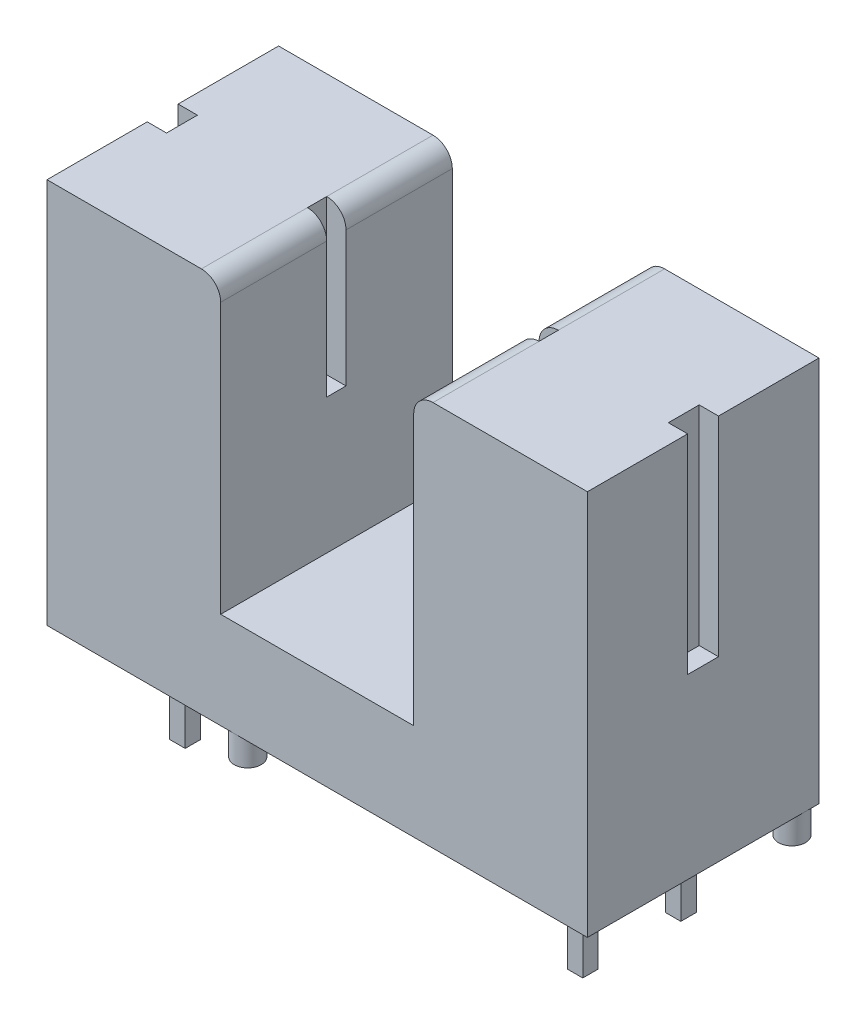
SolidWorks part; units mm, degrees
ref_plane "前视基准面" through (0, 0, 0) normal (0, 0, 1) x (1, 0, 0)
ref_plane "上视基准面" through (0, 0, 0) normal (0, 1, 0) x (1, 0, 0)
ref_plane "右视基准面" through (0, 0, 0) normal (1, 0, 0) x (0, 0, -1)
sketch "草图1" plane through (0, 0, 0) normal (0, 0, 1) x (1, 0, 0)
  line L0 (0, 6.704) -> (0, -11.7189) construction
  line L1 (-7, 5) -> (-2.5, 5)
  line L2 (-7, 5) -> (-7, -5)
  line L3 (-7, -5) -> (7, -5)
  line L4 (7, 5) -> (7, -5)
  line L5 (-7, 5) -> (7, -5) construction
  line L6 (-7, -5) -> (7, 5) construction
  line L7 (2.5, 5) -> (7, 5)
  line L9 (-2.5, 5) -> (-2.5, -2.5)
  line L10 (-2.5, -2.5) -> (2.5, -2.5)
  line L11 (2.5, 5) -> (2.5, -2.5)
  point P0 (0, 0)
  dimension "D1" = 14
  dimension "D2" = 10
  dimension "D3" = 5
  dimension "D4" = 2.5
extrude "凸台-拉伸1" add sketch "草图1" along normal blind 6
fillet "圆角1" radius 0.5 2 edges at (2.5, 5, 3) (-2.5, 5, 3)
sketch "草图2" plane through (0, -5, 0) normal (0, -1, 0) x (1, 0, 0)
  line L0 (-8.0802, 3) -> (8.1696, 3) construction
  line L1 (0, 6.3864) -> (0, -1.1649) construction
  line L3 (-5.15, 4.27) -> (5.15, 4.27) construction
  line L4 (-5.15, 4.27) -> (-5.15, 1.73) construction
  line L5 (-5.15, 1.73) -> (5.15, 1.73) construction
  line L6 (5.15, 4.27) -> (5.15, 1.73) construction
  line L7 (-5.15, 4.27) -> (5.15, 1.73) construction
  line L8 (-5.15, 1.73) -> (5.15, 4.27) construction
  line L9 (-5.35, 4.47) -> (-4.95, 4.47)
  line L10 (-5.35, 4.47) -> (-5.35, 4.07)
  line L11 (-5.35, 4.07) -> (-4.95, 4.07)
  line L12 (-4.95, 4.47) -> (-4.95, 4.07)
  line L13 (-5.35, 4.47) -> (-4.95, 4.07) construction
  line L14 (-5.35, 4.07) -> (-4.95, 4.47) construction
  line L15 (4.95, 4.47) -> (5.35, 4.47)
  line L16 (4.95, 4.47) -> (4.95, 4.07)
  line L17 (4.95, 4.07) -> (5.35, 4.07)
  line L18 (5.35, 4.47) -> (5.35, 4.07)
  line L19 (4.95, 4.47) -> (5.35, 4.07) construction
  line L20 (4.95, 4.07) -> (5.35, 4.47) construction
  line L21 (-5.35, 1.53) -> (-4.95, 1.53)
  line L22 (-5.35, 1.53) -> (-5.35, 1.93)
  line L23 (-5.35, 1.93) -> (-4.95, 1.93)
  line L24 (-4.95, 1.53) -> (-4.95, 1.93)
  line L25 (-5.35, 1.53) -> (-4.95, 1.93) construction
  line L26 (-5.35, 1.93) -> (-4.95, 1.53) construction
  line L27 (4.95, 1.93) -> (5.35, 1.93)
  line L28 (4.95, 1.93) -> (4.95, 1.53)
  line L29 (4.95, 1.53) -> (5.35, 1.53)
  line L30 (5.35, 1.93) -> (5.35, 1.53)
  line L31 (4.95, 1.93) -> (5.35, 1.53) construction
  line L32 (4.95, 1.53) -> (5.35, 1.93) construction
  point P4 (0, 3)
  dimension "D1" = 10.3
  dimension "D2" = 2.54
  dimension "D3" = 0.4
  dimension "D4" = 0.4
  dimension "D5" = 0.4
  dimension "D6" = 0.4
  dimension "D7" = 0.4
  dimension "D8" = 0.4
  dimension "D9" = 0.4
  dimension "D10" = 0.4
extrude "凸台-拉伸2" add sketch "草图2" along normal blind 2.5
sketch "草图3" plane through (-7, 0, 0) normal (-1, 0, 0) x (0, 0, 1)
  line L0 (3.0034, 5.5455) -> (3.0034, -0.195) construction
  line L1 (6, 5) -> (0, 5) construction
  line L2 (2.6034, 5) -> (3.4034, 5)
  line L3 (2.6034, 5) -> (2.6034, -0.4)
  line L4 (2.6034, -0.4) -> (3.4034, -0.4)
  line L5 (3.4034, 5) -> (3.4034, -0.4)
  dimension "D1" = 0.8
  dimension "D2" = 5.4
extrude "切除-拉伸1" cut sketch "草图3" against normal blind 0.5
sketch "草图4" plane through (7, 0, 0) normal (1, 0, 0) x (0, 0, -1)
  line L1 (-3.4034, 5) -> (-2.6034, 5)
  line L2 (-3.4034, 5) -> (-3.4034, -0.4)
  line L3 (-3.4034, -0.4) -> (-2.6034, -0.4)
  line L4 (-2.6034, 5) -> (-2.6034, -0.4)
extrude "切除-拉伸2" cut sketch "草图4" against normal blind 0.5
sketch "草图5" plane through (-2.5, 0, 0) normal (1, 0, 0) x (0, 0, -1)
  line L0 (-3.0034, 5.9062) -> (-3.0034, -8.6513) construction
  line L1 (-2.6034, 5) -> (-3.4034, 5) construction
  line L2 (-3.2534, 5) -> (-2.7534, 5)
  line L3 (-3.2534, 5) -> (-3.2534, 1)
  line L4 (-3.2534, 1) -> (-2.7534, 1)
  line L5 (-2.7534, 5) -> (-2.7534, 1)
  dimension "D1" = 0.5
  dimension "D2" = 4
extrude "切除-拉伸3" cut sketch "草图5" against normal blind 0.5
sketch "草图6" plane through (2.5, 0, 0) normal (-1, 0, 0) x (0, 0, 1)
  line L0 (3.4034, 5) -> (2.6034, 5) construction
  line L1 (3.2534, 1) -> (2.7534, 1)
  line L2 (3.2534, 1) -> (3.2534, 5)
  line L3 (3.2534, 5) -> (2.7534, 5)
  line L4 (2.7534, 1) -> (2.7534, 5)
extrude "切除-拉伸4" cut sketch "草图6" against normal blind 0.5
sketch "草图7" plane through (0, -5, 0) normal (0, -1, 0) x (1, 0, 0)
  line L0 (-7, 6) -> (7, 6) construction
  line L1 (0, 6.6897) -> (0, -1.6439) construction
  line L2 (7, 6) -> (7, 0) construction
  line L3 (-7, 0) -> (7, 0) construction
  line L4 (-2.5, 6) -> (-2.5, 0) construction
  circle A0 centre (-2.15, 5.65) radius 0.35
  circle A1 centre (6.65, 0.35) radius 0.35
  dimension "D1" = 0.7
  dimension "D2" = 0.7
extrude "凸台-拉伸3" add sketch "草图7" along normal blind 0.7
